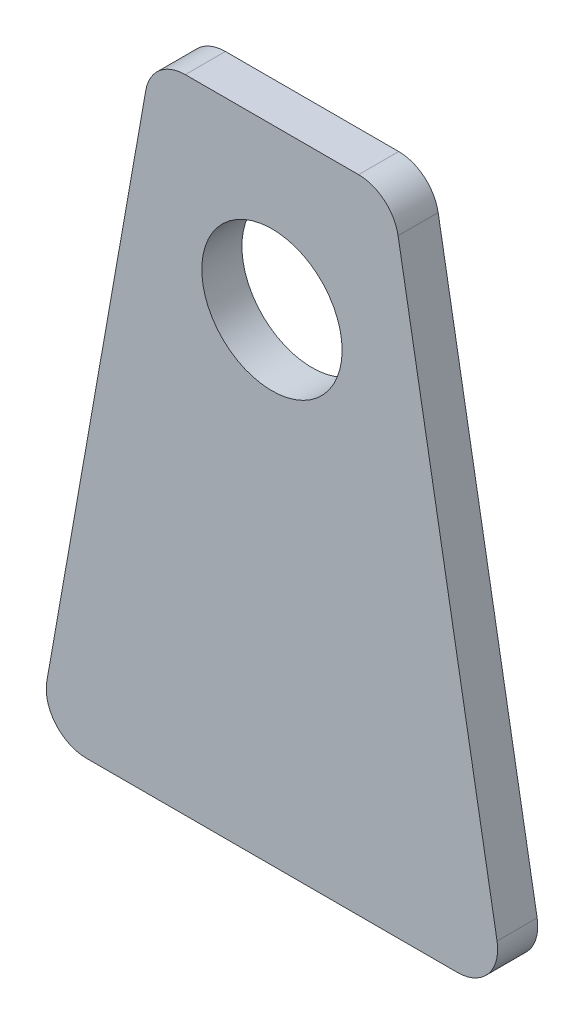
SolidWorks part; units mm, degrees
material "Plain Carbon Steel"
ref_plane "Front Plane" through (0, 0, 0) normal (0, 0, 1) x (1, 0, 0)
ref_plane "Top Plane" through (0, 0, 0) normal (0, 1, 0) x (1, 0, 0)
ref_plane "Right Plane" through (0, 0, 0) normal (1, 0, 0) x (0, 0, -1)
sketch "Layout" plane through (0, 0, 0) normal (0, 0, 1) x (1, 0, 0)
  line L0 (-329.0442, 0) -> (309.3606, 0) construction
  line L5 (1.3141, 7.4527) -> (16.9896, 96.3527)
  line L6 (23.2431, 101.6) -> (50.6865, 101.6)
  line L7 (56.9401, 96.3527) -> (72.6155, 7.4527)
  line L8 (7.5676, 0) -> (66.362, 0)
  circle A0 centre (36.9648, 76.2) radius 11.1125
  arc A8 (72.6155, 7.4527) -> (66.362, 0) centre (66.362, 6.35) cw
  arc A9 (1.3141, 7.4527) -> (7.5676, 0) centre (7.5676, 6.35) ccw
  arc A10 (16.9896, 96.3527) -> (23.2431, 101.6) centre (23.2431, 95.25) cw
  arc A11 (50.6865, 101.6) -> (56.9401, 96.3527) centre (50.6865, 95.25) cw
  point P2 (73.9296, 0)
  point P11 (0, 0)
  point P14 (17.9148, 101.6)
  point P20 (56.0148, 101.6)
  dimension "D9" = 22.225
  dimension "D2" = 6.35
  dimension "D1" = 101.6
  dimension "D4" = 80
  dimension "D5" = 38.1
  dimension "D6" = 25.4
  dimension "D7" = 19.05
extrude "Boss-Extrude1" add sketch "Layout" along normal blind 6.35
